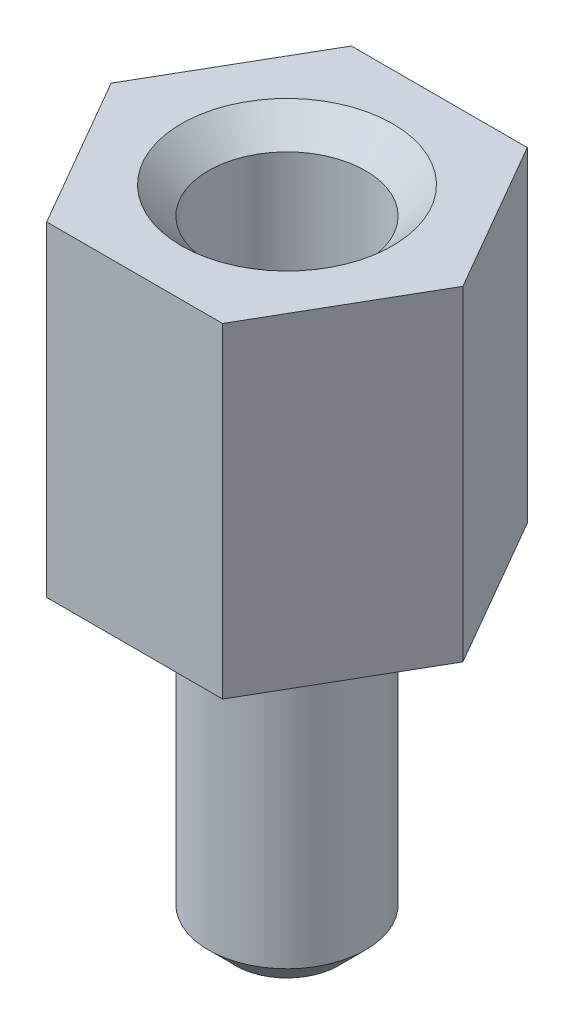
SolidWorks part; units mm, degrees
ref_plane "Front Plane" through (0, 0, 0) normal (0, 0, 1) x (1, 0, 0)
ref_plane "Top Plane" through (0, 0, 0) normal (0, 1, 0) x (1, 0, 0)
ref_plane "Right Plane" through (0, 0, 0) normal (1, 0, 0) x (0, 0, -1)
sketch "Sketch1" plane through (0, 0, 0) normal (0, 1, 0) x (1, 0, 0)
  line L1 (3.2447, 0) -> (1.6224, 2.81)
  line L2 (1.6224, 2.81) -> (-1.6224, 2.81)
  line L3 (-1.6224, 2.81) -> (-3.2447, 0)
  line L4 (-3.2447, 0) -> (-1.6224, -2.81)
  line L5 (-1.6224, -2.81) -> (1.6224, -2.81)
  line L6 (1.6224, -2.81) -> (3.2447, 0)
  circle A0 centre (0, 0) radius 2.81 construction
  dimension "D1" = 5.62
extrude "Boss-Extrude1" add sketch "Sketch1" along normal blind 6
sketch "Sketch2" plane through (0, 0, 0) normal (0, -1, 0) x (1, 0, 0)
  circle A0 centre (0, 0) radius 1.45
  dimension "D1" = 2.9
extrude "Boss-Extrude2" add sketch "Sketch2" along normal blind 6
sketch "Sketch3" plane through (0, 6, 0) normal (0, 1, 0) x (1, 0, 0)
  circle A0 centre (0, 0) radius 1.45
  circle A1 centre (0, 0) radius 1.45 construction
extrude "Cut-Extrude1" cut sketch "Sketch3" against normal blind 5
chamfer "Chamfer1" distance 0.5 angle 45 2 edges at (0, -6, -1.45) (0, 6, 1.45)
